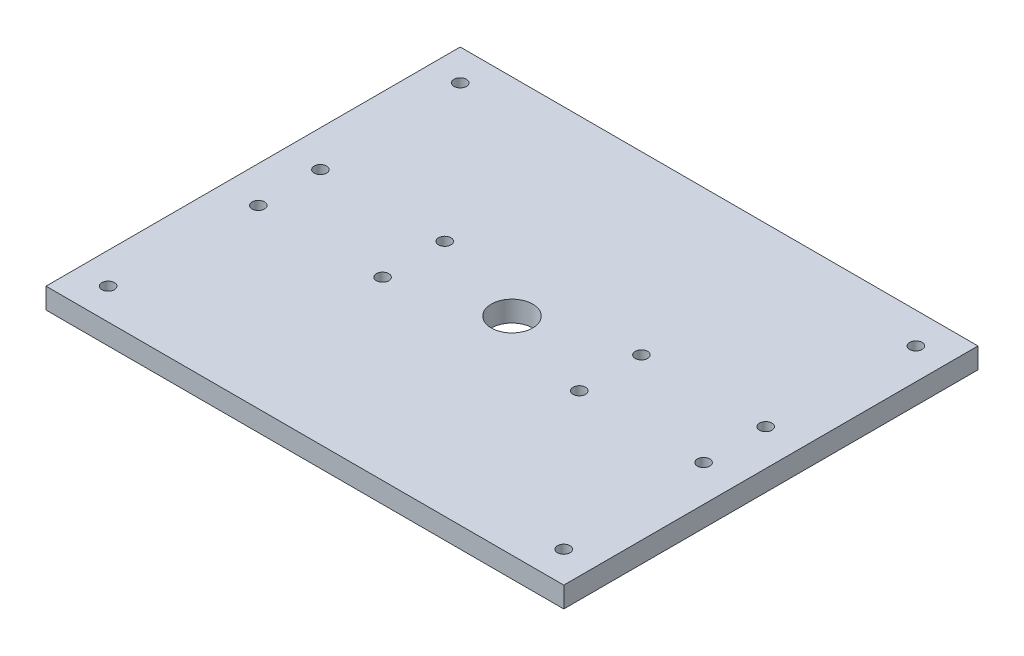
SolidWorks part; units mm, degrees
ref_plane "Front Plane" through (0, 0, 0) normal (0, 0, 1) x (1, 0, 0)
ref_plane "Top Plane" through (0, 0, 0) normal (0, 1, 0) x (1, 0, 0)
ref_plane "Right Plane" through (0, 0, 0) normal (1, 0, 0) x (0, 0, -1)
sketch "Sketch1" plane through (0, 0, 0) normal (0, 1, 0) x (1, 0, 0)
  line L1 (0, 0) -> (100, 0)
  line L2 (0, 0) -> (0, 80)
  line L3 (0, 80) -> (100, 80)
  line L4 (100, 0) -> (100, 80)
  dimension "D1" = 80
  dimension "D2" = 100
extrude "Boss-Extrude1" add sketch "Sketch1" along normal blind 4
hole_wizard "M2 Clearance Hole1" positions "Sketch5" profile "Sketch3" hole size "M2" standard "DIN"
sketch "Sketch5" plane through (0, 4, 0) normal (0, 1, 0) x (1, 0, 0)
  line L0 (7, 46) -> (7, 34) construction
  line L2 (7, 40) -> (0, 40) construction
  line L3 (0, 80) -> (0, 0) construction
  point P0 (7, 34)
  point P7 (31, 34)
  point P8 (31, 46)
  point P9 (7, 46)
  dimension "D3" = 24
  dimension "D4" = 12
  dimension "D5" = 7
  dimension "D1" = 2
  dimension "D2" = 2
sketch "Sketch3" plane through (7, 4, -34) normal (1, 0, 0) x (0, 0, 1)
  line L0 (0, 0) -> (0, 6)
  line L1 (0, 6) -> (1.2, 6)
  line L2 (1.2, 6) -> (1.2, 0)
  line L5 (1.2, 0) -> (0, 0)
  line L10 (0, 6) -> (-1.2, 6) construction
  line L11 (0, -6.35) -> (0, 107.95) construction
  dimension "Hole Dia." = 2.4
  dimension "Hole Depth" = 6
  dimension "Drill Angle" = 180
ref_plane "Plane1" through (50, 0, 0) normal (-1, 0, 0) x (0, 0, 1)
mirror "Mirror1" about plane through (50, 0, 0) normal (-1, 0, 0) of "M2 Clearance Hole1"
hole_wizard "M2 Clearance Hole2" positions "Sketch8" profile "Sketch7" hole size "M2" standard "DIN"
sketch "Sketch8" plane through (0, 4, 0) normal (0, 1, 0) x (1, 0, 0)
  line L0 (100, 80) -> (0, 80) construction
  line L1 (0, 80) -> (0, 0) construction
  line L2 (0, 0) -> (100, 0) construction
  line L3 (100, 0) -> (100, 80) construction
  point P0 (6, 74)
  point P10 (94, 74)
  point P11 (94, 6)
  point P12 (6, 6)
  dimension "D1" = 6
  dimension "D2" = 6
  dimension "D5" = 6
  dimension "D6" = 6
  dimension "D3" = 2
  dimension "D4" = 2
sketch "Sketch7" plane through (6, 4, -74) normal (1, 0, 0) x (0, 0, 1)
  line L0 (0, 0) -> (0, 6)
  line L1 (0, 6) -> (1.2, 6)
  line L2 (1.2, 6) -> (1.2, 0)
  line L5 (1.2, 0) -> (0, 0)
  line L10 (0, 6) -> (-1.2, 6) construction
  line L11 (0, -6.35) -> (0, 107.95) construction
  dimension "Hole Dia." = 2.4
  dimension "Hole Depth" = 6
  dimension "Drill Angle" = 180
hole_wizard "Ø8.0mm Dowel Hole1" positions "Sketch12" profile "Sketch11" hole size "Ø8.0" standard "DIN" end condition through all
sketch "Sketch12" plane through (0, 4, 0) normal (0, 1, 0) x (1, 0, 0)
  line L0 (0, 80) -> (100, 0) construction
  line L1 (100, 0) -> (100, 80) construction
  line L2 (100, 80) -> (0, 0) construction
  point P13 (50, 40)
sketch "Sketch11" plane through (50, 4, -40) normal (1, 0, 0) x (0, 0, 1)
  line L0 (0, 0) -> (0, 4)
  line L1 (0, 4) -> (4, 4)
  line L2 (4, 4) -> (4, 0)
  line L5 (4, 0) -> (0, 0)
  line L11 (0, -6.35) -> (0, 107.95) construction
  dimension "Thru Hole Dia." = 8
  dimension "Thru Hole Depth" = 4
